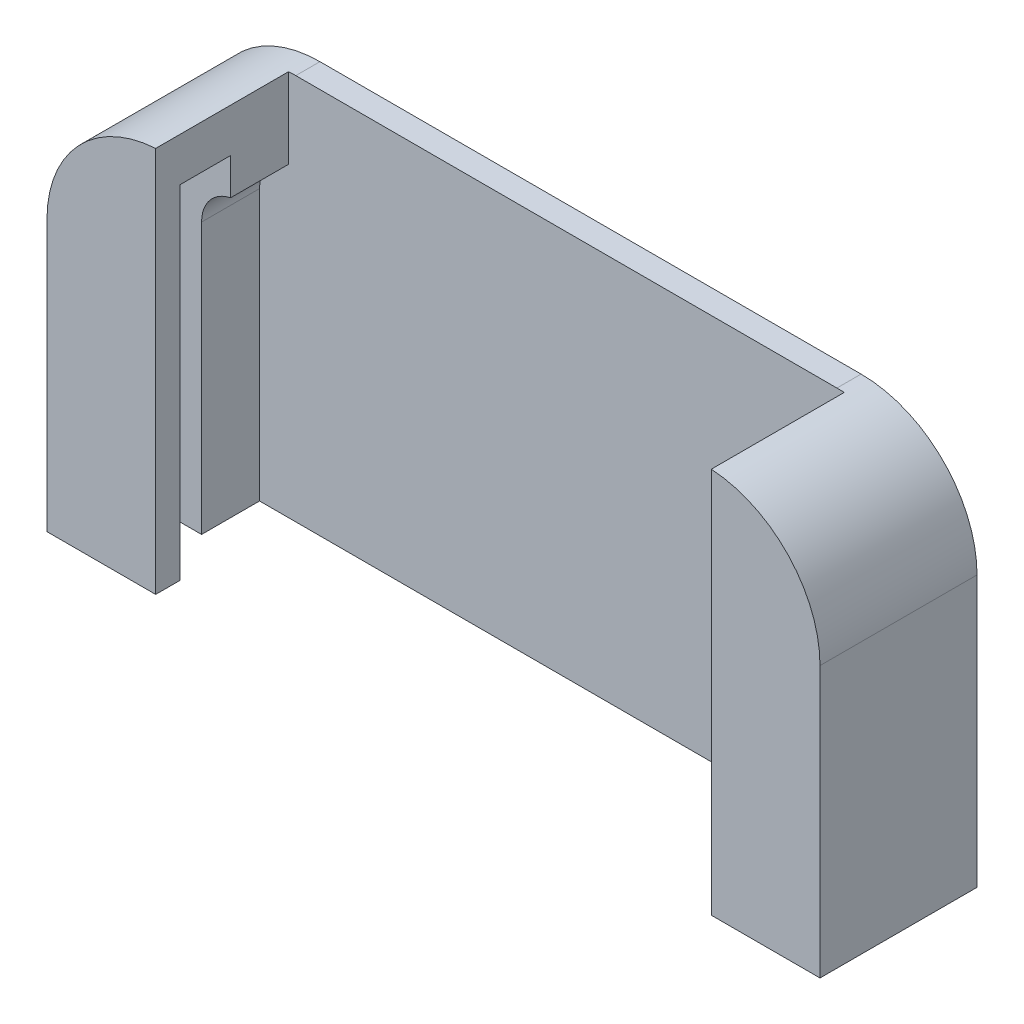
SolidWorks part; units mm, degrees
material "policarbonato"
ref_plane "Alzado" through (0, 0, 0) normal (0, 0, 1) x (1, 0, 0)
ref_plane "Planta" through (0, 0, 0) normal (0, 1, 0) x (1, 0, 0)
ref_plane "Vista lateral" through (0, 0, 0) normal (1, 0, 0) x (0, 0, -1)
sketch "Sketch3" plane through (0, 0, 0) normal (0, 0, 1) x (1, 0, 0)
  line L1 (0, 0) -> (32, 0)
  line L2 (0, 0) -> (0, 11.2)
  line L3 (4.8, 16) -> (27.2, 16)
  line L4 (32, 0) -> (32, 11.2)
  arc A0 (27.2, 16) -> (32, 11.2) centre (27.2, 11.2) cw
  arc A1 (0, 11.2) -> (4.8, 16) centre (4.8, 11.2) cw
  point P7 (32, 16)
  point P10 (0, 16)
  dimension "D3" = 4.8
  dimension "D1" = 32
  dimension "D2" = 16
extrude "Boss-Extrude2" add sketch "Sketch3" along normal blind 5.5
sketch "Sketch4" plane through (0, 0, 5.5) normal (0, 0, 1) x (1, 0, 0)
  line L4 (0, 0) -> (32, 0) construction
  line L5 (1.8, 0) -> (30.2, 0)
  line L6 (27.2, 14.2) -> (4.8, 14.2)
  line L7 (1.8, 11.2) -> (1.8, 0)
  line L8 (27.2, 16) -> (4.8, 16) construction
  line L9 (0, 11.2) -> (0, 0) construction
  line L10 (32, 0) -> (32, 11.2) construction
  line L14 (30.2, 0) -> (30.2, 11.2)
  arc A2 (4.8, 14.2) -> (1.8, 11.2) centre (4.8, 11.2) ccw
  arc A6 (30.2, 11.2) -> (27.2, 14.2) centre (27.2, 11.2) ccw
  dimension "D1" = 3
  dimension "D2" = 1.8
  dimension "D3" = 1.8
  dimension "D4" = 1.8
extrude "Cut-Extrude1" cut sketch "Sketch4" against normal offset from surface (4.5 mm away) 1 up to face at (16, 9.398, 0)
sketch "Sketch5" plane through (0, 0, 1) normal (0, 0, 1) x (1, 0, 0)
  line L0 (1.8, 11.2) -> (1.8, 0) construction
  line L3 (27.2, 14.2) -> (4.8, 14.2) construction
  line L4 (30.2, 0) -> (30.2, 11.2) construction
  line L5 (1.8, 11.2) -> (1.8, 0)
  line L6 (27.2, 14.2) -> (4.8, 14.2)
  line L7 (30.2, 0) -> (30.2, 11.2)
  line L8 (28.7, 0) -> (28.7, 11.2)
  line L9 (27.2, 12.7) -> (4.8, 12.7)
  line L10 (3.3, 11.2) -> (3.3, 0)
  line L11 (1.8, 0) -> (3.3, 0)
  line L12 (28.7, 0) -> (30.2, 0)
  arc A1 (4.8, 14.2) -> (1.8, 11.2) centre (4.8, 11.2) ccw construction
  arc A2 (30.2, 11.2) -> (27.2, 14.2) centre (27.2, 11.2) ccw construction
  arc A3 (4.8, 14.2) -> (1.8, 11.2) centre (4.8, 11.2) ccw
  arc A4 (30.2, 11.2) -> (27.2, 14.2) centre (27.2, 11.2) ccw
  arc A5 (28.7, 11.2) -> (27.2, 12.7) centre (27.2, 11.2) ccw
  arc A6 (4.8, 12.7) -> (3.3, 11.2) centre (4.8, 11.2) ccw
  dimension "D1" = 1.5
extrude "Boss-Extrude3" add sketch "Sketch5" along normal blind 2.4
sketch "Croquis1" plane through (0, 0, 5.5) normal (0, 0, 1) x (1, 0, 0)
  line L2 (16, 26.66) -> (16, 0) construction
  line L5 (4.5, 0) -> (4.5, 15.9906)
  line L6 (27.5, 15.9906) -> (27.5, 0)
  line L7 (3.3, 0) -> (28.7, 0) construction
  line L8 (0, 0) -> (1.8, 0)
  line L9 (1.8, 0) -> (1.8, 11.2)
  line L10 (4.8, 14.2) -> (27.2, 14.2)
  line L11 (30.2, 11.2) -> (30.2, 0)
  line L12 (30.2, 0) -> (32, 0)
  line L13 (32, 0) -> (32, 11.2)
  line L14 (27.2, 16) -> (4.8, 16)
  line L15 (0, 11.2) -> (0, 0)
  line L16 (0, 0) -> (4.5, 0)
  line L20 (27.5, 0) -> (32, 0)
  line L21 (32, 0) -> (32, 11.2)
  line L23 (0, 11.2) -> (0, 0)
  arc A4 (4.8, 14.2) -> (1.8, 11.2) centre (4.8, 11.2) ccw
  arc A5 (30.2, 11.2) -> (27.2, 14.2) centre (27.2, 11.2) ccw
  arc A6 (32, 11.2) -> (27.2, 16) centre (27.2, 11.2) ccw
  arc A7 (4.8, 16) -> (0, 11.2) centre (4.8, 11.2) ccw
  arc A10 (32, 11.2) -> (27.5, 15.9906) centre (27.2, 11.2) ccw
  arc A11 (4.5, 15.9906) -> (0, 11.2) centre (4.8, 11.2) ccw
  dimension "D2" = 23
  dimension "D1" = 0
extrude "Saliente-Extruir1" add sketch "Croquis1" along normal blind 1
sketch "Croquis3" plane through (0, 16, 0) normal (0, 1, 0) x (1, 0, 0)
  line L0 (4.5, -6.5) -> (4.5, -5.5) construction
  line L1 (4.5, -5.5) -> (27.5, -5.5)
  line L2 (4.5, -5.5) -> (4.5, -1)
  line L3 (4.5, -1) -> (27.5, -1)
  line L4 (27.5, -5.5) -> (27.5, -1)
  line L5 (27.2, -5.5) -> (4.8, -5.5) construction
  line L6 (27.5, -6.5) -> (27.5, -5.5) construction
  line L10 (4.8, -1) -> (27.2, -1) construction
extrude "Cortar-Extruir3" cut sketch "Croquis3" against normal up to next
